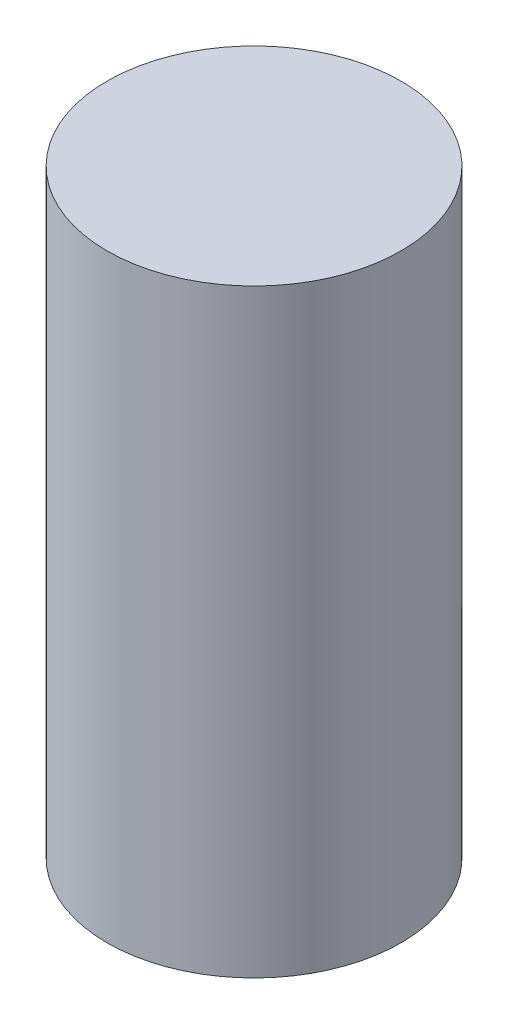
SolidWorks part; units mm, degrees
ref_plane "Plan de face" through (0, 0, 0) normal (0, 0, 1) x (1, 0, 0)
ref_plane "Plan de dessus" through (0, 0, 0) normal (0, 1, 0) x (1, 0, 0)
ref_plane "Plan de droite" through (0, 0, 0) normal (1, 0, 0) x (0, 0, -1)
other "Centre de masse"
sketch "Esquisse1" plane through (0, 0, 0) normal (0, 1, 0) x (1, 0, 0)
  circle A0 centre (0, 0) radius 73.61
  dimension "D1" = 147.22
extrude "Boss.-Extru.1" add sketch "Esquisse1" along normal blind 300
